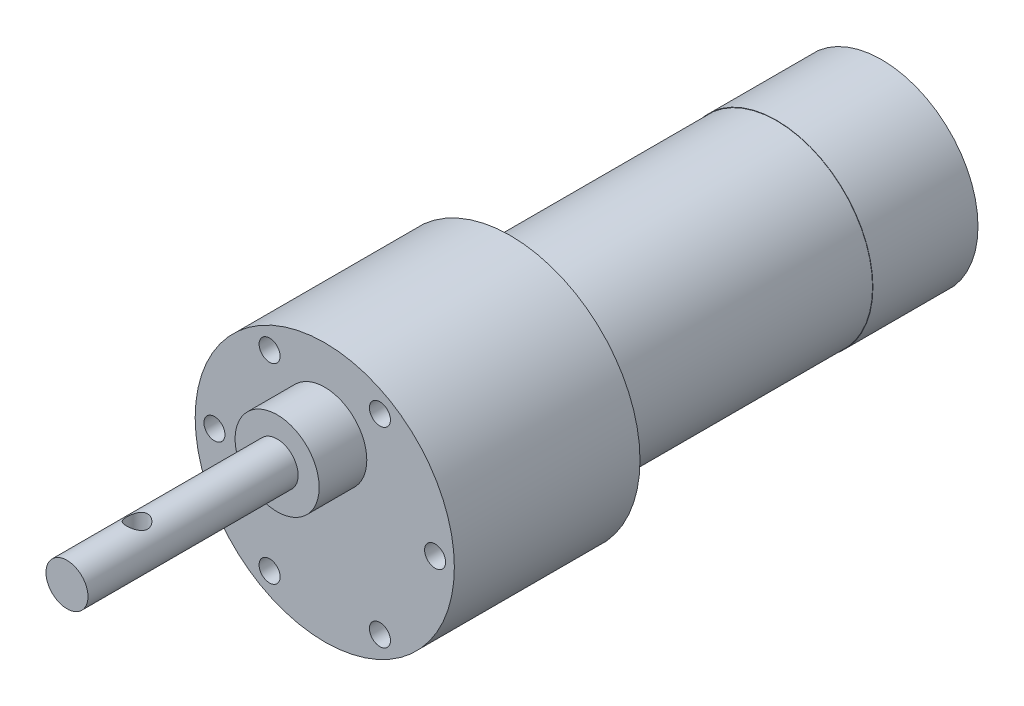
SolidWorks part; units mm, degrees
ref_plane "Front Plane" through (0, 0, 0) normal (0, 0, 1) x (1, 0, 0)
ref_plane "Top Plane" through (0, 0, 0) normal (0, 1, 0) x (1, 0, 0)
ref_plane "Right Plane" through (0, 0, 0) normal (1, 0, 0) x (0, 0, -1)
sketch "Sketch1" plane through (0, 0, 0) normal (0, 0, 1) x (1, 0, 0)
  circle A0 centre (0, 0) radius 18.5
  dimension "D1" = 37
extrude "Boss-Extrude1" add sketch "Sketch1" along normal blind 26.5
sketch "Sketch2" plane through (0, 0, 0) normal (0, 0, -1) x (-1, 0, 0)
  circle A0 centre (0, 0) radius 13.7
  dimension "D1" = 27.4
extrude "Boss-Extrude2" add sketch "Sketch2" along normal blind 38
sketch "Sketch3" plane through (0, 0, 26.5) normal (0, 0, 1) x (1, 0, 0)
  circle A0 centre (0, 7) radius 6
  dimension "D2" = 12
  dimension "D1" = 7
extrude "Boss-Extrude3" add sketch "Sketch3" along normal blind 6.8
sketch "Sketch4" plane through (0, 0, 33.3) normal (0, 0, 1) x (1, 0, 0)
  circle A0 centre (0, 7) radius 3
  circle A1 centre (0, 7) radius 6 construction
  dimension "D1" = 6
extrude "Boss-Extrude4" add sketch "Sketch4" along normal blind 30
sketch "Sketch5" plane through (0, 0, 26.5) normal (0, 0, 1) x (1, 0, 0)
  circle A0 centre (15.75, 0) radius 1.5
  dimension "D1" = 3
  dimension "D2" = 15.75
extrude "Cut-Extrude1" cut sketch "Sketch5" against normal blind 6
pattern_circular "CirPattern1" count 6 over 360 about axis through (0, 0, 0) along (0, 0, 1) of "Cut-Extrude1"
sketch "Sketch6" plane through (0, 0, -38) normal (0, 0, -1) x (-1, 0, 0)
  circle A0 centre (0, 0) radius 13.75
  dimension "D1" = 27.5
extrude "Boss-Extrude5" add sketch "Sketch6" along normal blind 15
sketch "Sketch7" plane through (0, 0, 0) normal (0, 1, 0) x (1, 0, 0)
  line L0 (-3, -63.3) -> (3, -63.3) construction
  circle A0 centre (0, -53.3) radius 1.5
  dimension "D1" = 3
  dimension "D2" = 10
extrude "Cut-Extrude2" cut sketch "Sketch7" along normal through all
